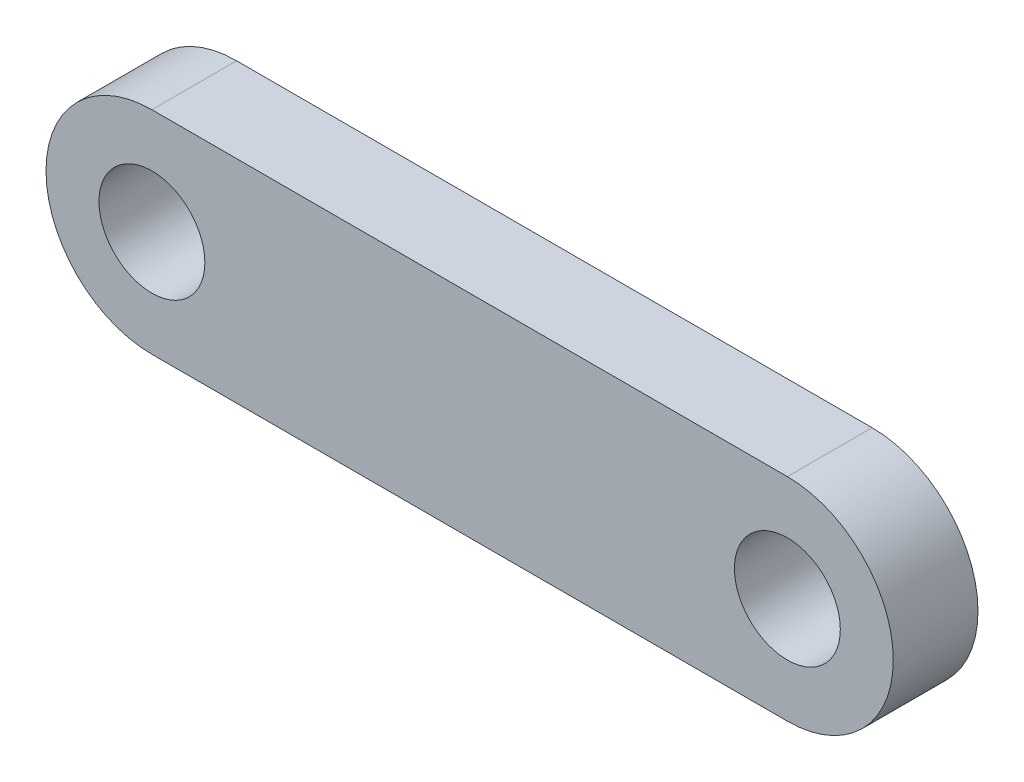
SolidWorks part; units mm, degrees
ref_plane "Plan de face" through (0, 0, 0) normal (0, 0, 1) x (1, 0, 0)
ref_plane "Plan de dessus" through (0, 0, 0) normal (0, 1, 0) x (1, 0, 0)
ref_plane "Plan de droite" through (0, 0, 0) normal (1, 0, 0) x (0, 0, -1)
sketch "Esquisse1" plane through (0, 0, 0) normal (0, 0, 1) x (1, 0, 0)
  line L0 (0, 0) -> (30, 0) construction
  line L1 (0, 5) -> (30, 5)
  line L2 (0, -5) -> (30, -5)
  arc A0 (0, 5) -> (0, -5) centre (0, 0) ccw
  arc A1 (30, -5) -> (30, 5) centre (30, 0) ccw
  circle A2 centre (30, 0) radius 2.5
  circle A3 centre (0, 0) radius 2.5
  point P3 (15, 0)
  point P8 (-5, 0)
  point P9 (35, 0)
  dimension "D2" = 5
  dimension "D3" = 5
  dimension "D4" = 5
  dimension "D1" = 40
extrude "Boss.-Extru.1" add sketch "Esquisse1" along normal blind 4
